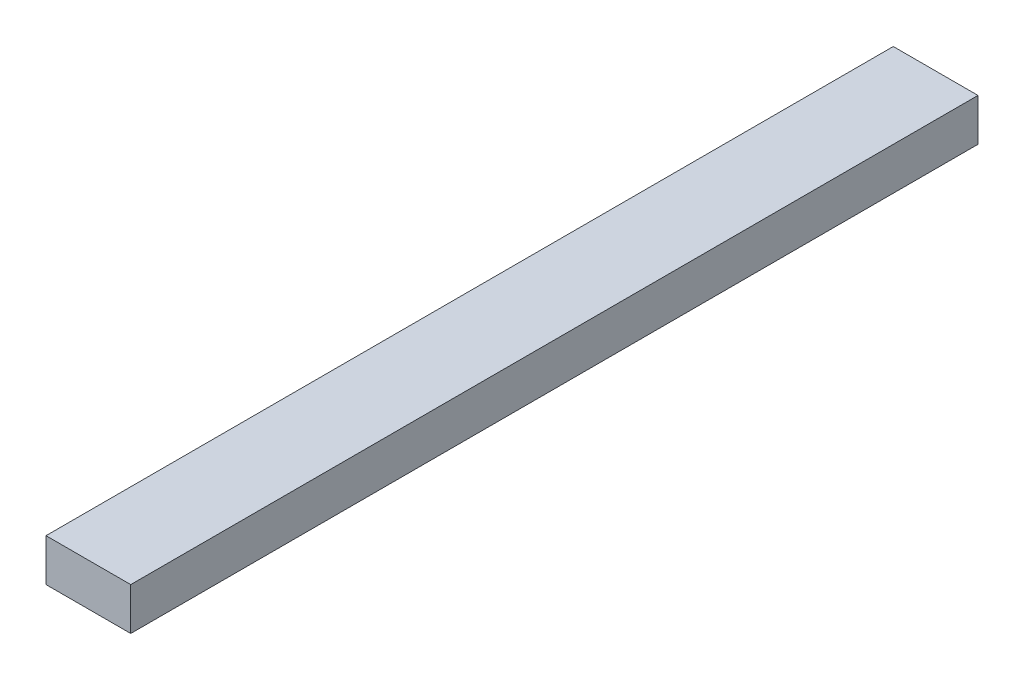
SolidWorks part; units mm, degrees
ref_plane "Front" through (0, 0, 0) normal (0, 0, 1) x (1, 0, 0)
ref_plane "Top" through (0, 0, 0) normal (0, 1, 0) x (1, 0, 0)
ref_plane "Right" through (0, 0, 0) normal (1, 0, 0) x (0, 0, -1)
sketch "Sketch1" plane through (0, 0, 0) normal (0, 0, 1) x (1, 0, 0)
  line L1 (0, 0) -> (-2.54, 0)
  line L2 (0, 0) -> (0, 1.27)
  line L3 (0, 1.27) -> (-2.54, 1.27)
  line L4 (-2.54, 0) -> (-2.54, 1.27)
  dimension "D1" = 2.54
  dimension "D2" = 1.27
extrude "Boss-Extrude1" add sketch "Sketch1" along normal blind 25.4
sketch "Sketch2" plane through (0, 0, 0) normal (0, -1, 0) x (-1, 0, 0)
  line L0 (2.54, -25.4) -> (2.54, 0) construction
  line L1 (2.54, 0) -> (0, 0) construction
  circle A0 centre (1.27, -1.27) radius 0.4445
  dimension "D1" = 0.889
  dimension "D2" = 1.27
  dimension "D3" = 1.27
